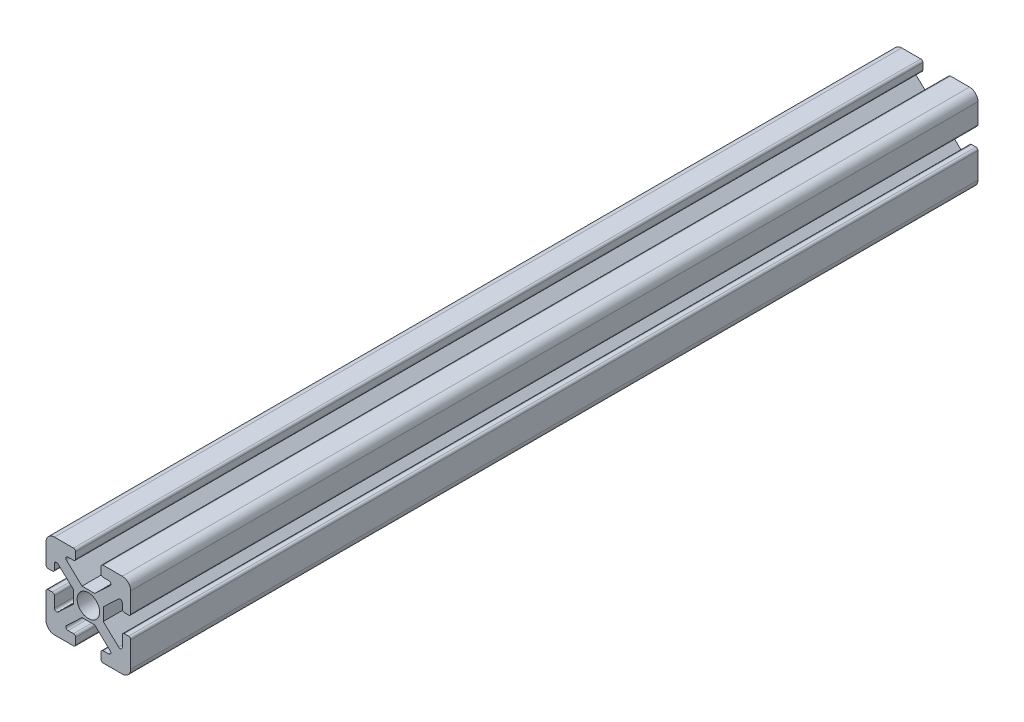
SolidWorks part; units mm, degrees
ref_plane "Front Plane" through (0, 0, 0) normal (0, 0, 1) x (1, 0, 0)
ref_plane "Top Plane" through (0, 0, 0) normal (0, 1, 0) x (1, 0, 0)
ref_plane "Right Plane" through (0, 0, 0) normal (1, 0, 0) x (0, 0, -1)
sketch "Sketch2" plane through (0, 0, 0) normal (0, 0, 1) x (1, 0, 0)
  line L0 (0, 2) -> (0, 8.0075)
  line L1 (2, 20) -> (6.5, 20)
  line L2 (20, 18) -> (20, 13.3075)
  line L3 (18, 0) -> (13.5, 0)
  line L4 (10, 0.2965) -> (10, 6.7965) construction
  line L5 (-0.015, 9.9158) -> (6.485, 9.9158) construction
  line L6 (18.5, 8.5075) -> (19.5, 8.5075)
  line L7 (18.5, 12.8075) -> (19.5, 12.8075)
  line L8 (13, 19.5) -> (13, 18.0175)
  line L9 (7, 19.5) -> (7, 18.0175)
  line L10 (2, 14.5732) -> (2, 13.3075)
  line L11 (5.2, 2.5071) -> (6.5, 2.5071)
  line L12 (18, 5.4513) -> (18, 8.0075)
  line L13 (14.8, 17.5175) -> (13.5, 17.5175)
  line L14 (1.5, 12.8075) -> (0.5, 12.8075)
  line L15 (13.5, 20) -> (18, 20)
  line L16 (6.5, 17.5175) -> (5.2, 17.5175)
  line L17 (20, 8.0075) -> (20, 2)
  line L18 (18, 13.3075) -> (18, 14.5732)
  line L19 (0, 13.3075) -> (0, 18)
  line L20 (2, 8.0075) -> (2, 5.4513)
  line L21 (6.5, 0) -> (2, 0)
  line L22 (13.5, 2.5071) -> (14.8, 2.5071)
  line L23 (1.5, 8.5075) -> (0.5, 8.5075)
  line L24 (13, 0.5) -> (13, 2.0071)
  line L25 (7, 2.0071) -> (7, 0.5)
  line L26 (17.1575, 14.9375) -> (13.515, 11.5123)
  line L27 (15.1425, 16.6533) -> (11.5, 13.228)
  line L28 (4.8575, 16.6533) -> (8.5, 13.228)
  line L29 (2.8425, 14.9375) -> (6.485, 11.5123)
  line L30 (13.515, 8.5123) -> (17.1575, 5.0871)
  line L31 (8.5, 6.7965) -> (11.5, 6.7965)
  line L32 (6.485, 8.5123) -> (6.485, 11.5123)
  line L33 (8.5, 13.228) -> (11.5, 13.228)
  line L34 (13.515, 8.5123) -> (13.515, 11.5123)
  line L37 (6.485, 8.5123) -> (2.8425, 5.0871)
  line L38 (13.515, 9.9158) -> (19.985, 9.9158) construction
  line L39 (11.5, 6.7965) -> (15.1425, 3.3713)
  line L41 (8.5, 6.7965) -> (4.8575, 3.3713)
  line L43 (10.0737, 13.228) -> (10.0737, 19.728) construction
  circle A0 centre (10, 10) radius 2.65
  arc A1 (0, 18) -> (2, 20) centre (2, 18) cw
  arc A2 (0, 2) -> (2, 0) centre (2, 2) ccw
  arc A3 (20, 2) -> (18, 0) centre (18, 2) cw
  arc A4 (18, 20) -> (20, 18) centre (18, 18) cw
  arc A5 (19.5, 8.5075) -> (20, 8.0075) centre (19.5, 8.0075) cw
  arc A6 (0.5, 8.5075) -> (0, 8.0075) centre (0.5, 8.0075) ccw
  arc A7 (0.5, 12.8075) -> (0, 13.3075) centre (0.5, 13.3075) cw
  arc A8 (13, 19.5) -> (13.5, 20) centre (13.5, 19.5) cw
  arc A9 (7, 19.5) -> (6.5, 20) centre (6.5, 19.5) ccw
  arc A10 (18, 8.0075) -> (18.5, 8.5075) centre (18.5, 8.0075) cw
  arc A11 (18.5, 12.8075) -> (18, 13.3075) centre (18.5, 13.3075) cw
  arc A12 (19.5, 12.8075) -> (20, 13.3075) centre (19.5, 13.3075) ccw
  arc A13 (7, 18.0175) -> (6.5, 17.5175) centre (6.5, 18.0175) cw
  arc A14 (13.5, 17.5175) -> (13, 18.0175) centre (13.5, 18.0175) cw
  arc A15 (2, 13.3075) -> (1.5, 12.8075) centre (1.5, 13.3075) cw
  arc A16 (2, 8.0075) -> (1.5, 8.5075) centre (1.5, 8.0075) ccw
  arc A17 (6.5, 2.5071) -> (7, 2.0071) centre (6.5, 2.0071) cw
  arc A18 (7, 0.5) -> (6.5, 0) centre (6.5, 0.5) cw
  arc A19 (13.5, 2.5071) -> (13, 2.0071) centre (13.5, 2.0071) ccw
  arc A20 (13, 0.5) -> (13.5, 0) centre (13.5, 0.5) ccw
  arc A21 (17.1575, 5.0871) -> (18, 5.4513) centre (17.5, 5.4513) ccw
  arc A22 (14.8, 2.5071) -> (15.1425, 3.3713) centre (14.8, 3.0071) ccw
  arc A23 (5.2, 2.5071) -> (4.8575, 3.3713) centre (5.2, 3.0071) cw
  arc A24 (2, 5.4513) -> (2.8425, 5.0871) centre (2.5, 5.4513) ccw
  arc A25 (2, 14.5732) -> (2.8425, 14.9375) centre (2.5, 14.5732) cw
  arc A26 (4.8575, 16.6533) -> (5.2, 17.5175) centre (5.2, 17.0175) cw
  arc A27 (17.1575, 14.9375) -> (18, 14.5732) centre (17.5, 14.5732) cw
  arc A28 (14.8, 17.5175) -> (15.1425, 16.6533) centre (14.8, 17.0175) cw
  dimension "D3" = 2
  dimension "D8" = 0.5
  dimension "D4" = 0.5
  dimension "D5" = 0.5
  dimension "D6" = 0.5
  dimension "D7" = 0.5
  dimension "D9" = 5.3
  dimension "D12" = 2
  dimension "D13" = 5
  dimension "D14" = 1.3
  dimension "D10" = 3
  dimension "D11" = 2
  dimension "D15" = 1.3
  dimension "D16" = 1.3
  dimension "D17" = 6
  dimension "D18" = 5.3
  dimension "D19" = 10
  dimension "D20" = 10
  dimension "D21" = 133.239
extrude "Boss-Extrude1" add sketch "Sketch2" along normal blind 200
